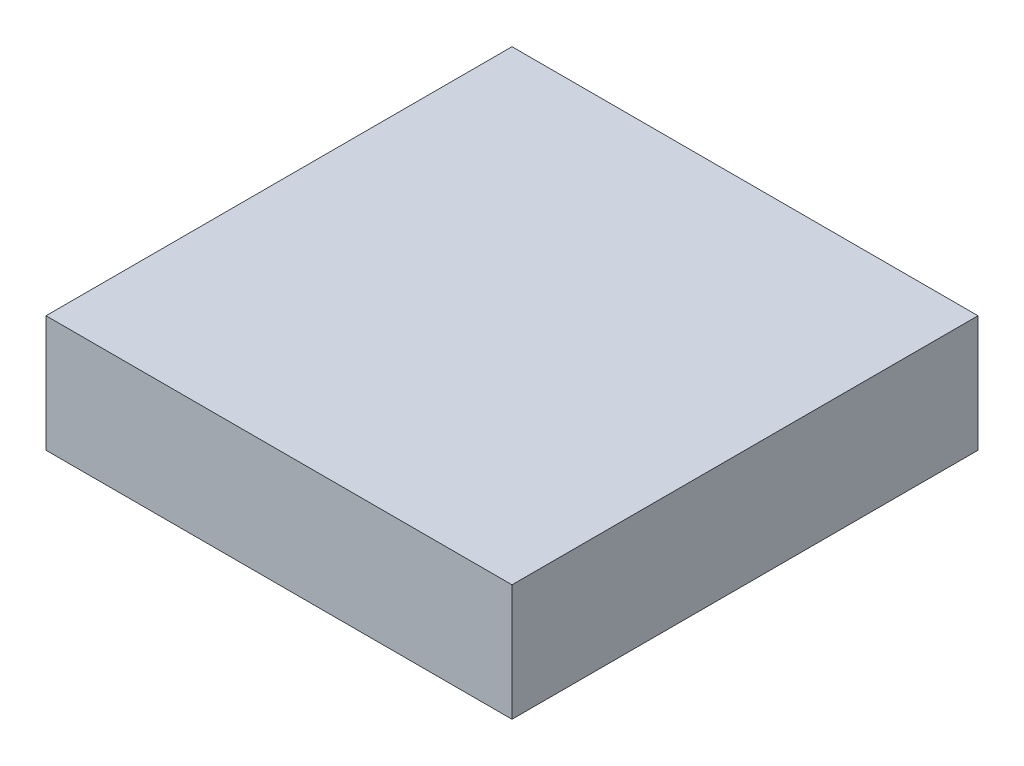
SolidWorks part; units mm, degrees
material "Pino"
ref_plane "Alzado" through (0, 0, 0) normal (0, 0, 1) x (1, 0, 0)
ref_plane "Planta" through (0, 0, 0) normal (0, 1, 0) x (1, 0, 0)
ref_plane "Vista lateral" through (0, 0, 0) normal (1, 0, 0) x (0, 0, -1)
sketch "Croquis1" plane through (0, 0, 0) normal (0, 1, 0) x (1, 0, 0)
  line L1 (-49.412, -30.8131) -> (52.188, -30.8131)
  line L2 (-49.412, -30.8131) -> (-49.412, 70.7869)
  line L3 (-49.412, 70.7869) -> (52.188, 70.7869)
  line L4 (52.188, -30.8131) -> (52.188, 70.7869)
  dimension "D1" = 101.6
  dimension "D2" = 101.6
extrude "Saliente-Extruir1" add sketch "Croquis1" along normal blind 25.4
